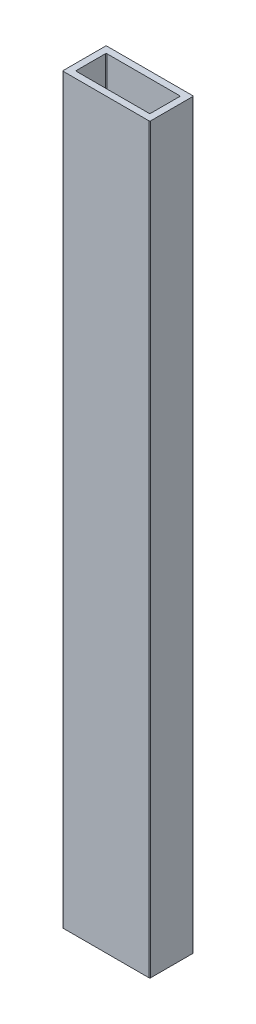
SolidWorks part; units mm, degrees
ref_plane "Спереди" through (0, 0, 0) normal (0, 0, 1) x (1, 0, 0)
ref_plane "Сверху" through (0, 0, 0) normal (0, 1, 0) x (1, 0, 0)
ref_plane "Справа" through (0, 0, 0) normal (1, 0, 0) x (0, 0, -1)
sketch "Эскиз1" plane through (0, 0, 0) normal (0, 1, 0) x (1, 0, 0)
  line L0 (8.5, 3.5) -> (-8.5, 3.5)
  line L1 (10, 5) -> (-10, 5)
  line L2 (10, 5) -> (10, -5)
  line L3 (10, -5) -> (-10, -5)
  line L4 (-10, 5) -> (-10, -5)
  line L5 (10, 5) -> (-10, -5) construction
  line L6 (10, -5) -> (-10, 5) construction
  line L7 (-8.5, 3.5) -> (-8.5, -3.5)
  line L8 (8.5, -3.5) -> (-8.5, -3.5)
  line L9 (8.5, 3.5) -> (8.5, -3.5)
  point P0 (0, 0)
  dimension "D1" = 20
  dimension "D2" = 10
  dimension "D3" = 1.5
extrude "Бобышка-Вытянуть1" add sketch "Эскиз1" along normal blind 170
fillet "Скругление1" radius 0.2 8 edges at (-10, 85, 5) (10, 85, -5) (8.5, 85, -3.5) (8.5, 85, 3.5) (-8.5, 85, 3.5) (-8.5, 85, -3.5) (-10, 85, -5) (10, 85, 5)
